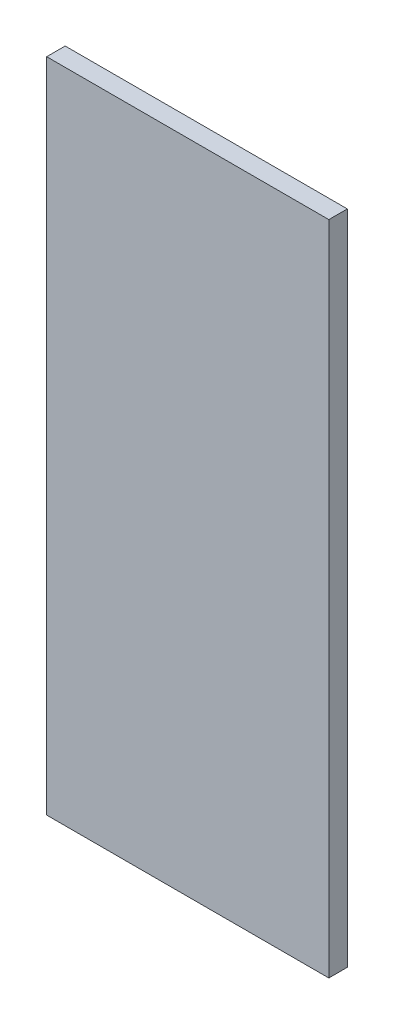
SolidWorks part; units mm, degrees
ref_plane "Alzado" through (0, 0, 0) normal (0, 0, 1) x (1, 0, 0)
ref_plane "Planta" through (0, 0, 0) normal (0, 1, 0) x (1, 0, 0)
ref_plane "Vista lateral" through (0, 0, 0) normal (1, 0, 0) x (0, 0, -1)
sketch "Croquis1" plane through (0, 0, 0) normal (0, 0, 1) x (1, 0, 0)
  line L1 (0, 0) -> (61, 0)
  line L2 (0, 0) -> (0, 142)
  line L3 (0, 142) -> (61, 142)
  line L4 (61, 0) -> (61, 142)
  dimension "D1" = 61
  dimension "D2" = 142
extrude "Saliente-Extruir1" add sketch "Croquis1" along normal blind 4
